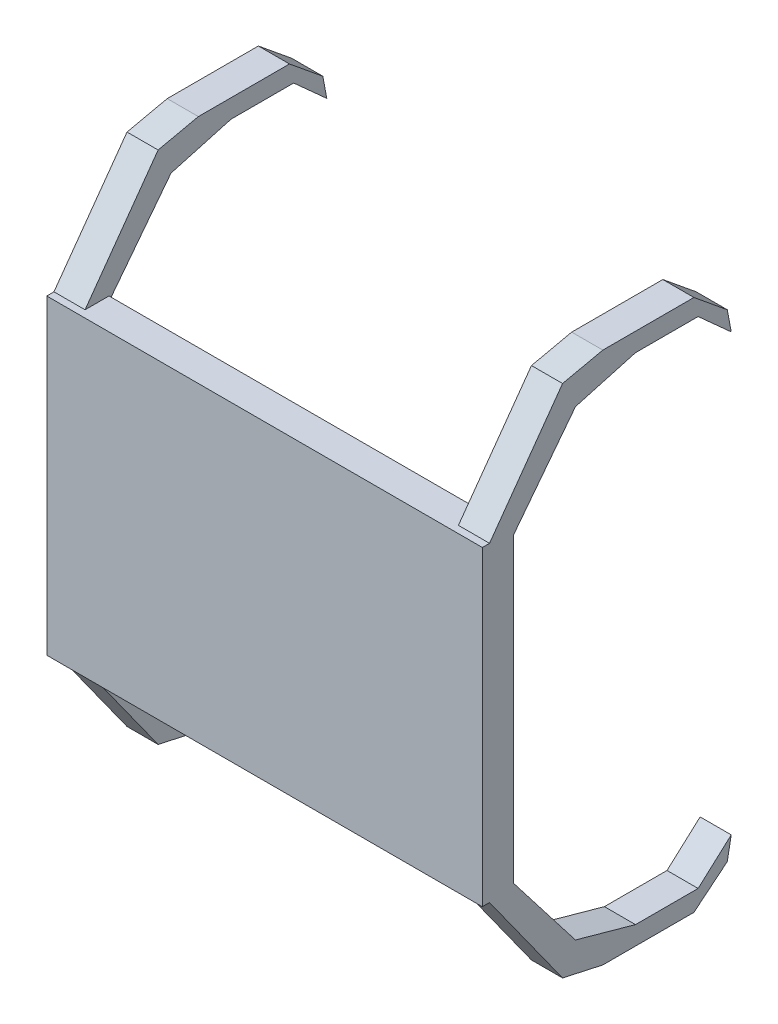
SolidWorks part; units mm, degrees
ref_plane "Front Plane" through (0, 0, 0) normal (0, 0, 1) x (1, 0, 0)
ref_plane "Top Plane" through (0, 0, 0) normal (0, 1, 0) x (1, 0, 0)
ref_plane "Right Plane" through (0, 0, 0) normal (1, 0, 0) x (0, 0, -1)
sketch "Sketch1" plane through (0, 0, 0) normal (0, 0, 1) x (1, 0, 0)
  line L0 (0, 0) -> (0, 23754.0671) construction
  line L1 (0, 0) -> (23754.0671, 0) construction
  line L2 (-35, 25) -> (35, 25)
  line L3 (35, 25) -> (35, -25)
  line L4 (-35, -25) -> (35, -25)
  line L5 (-35, 25) -> (-35, -25)
  point P9 (35, 0)
  point P11 (0, -25)
  point P12 (0, 25)
  dimension "D1" = 50
  dimension "D2" = 70
extrude "Boss-Extrude1" add sketch "Sketch1" along normal blind 5
sketch "Sketch2" plane through (-35, 0, 0) normal (-1, 0, 0) x (0, 0, 1)
  line L0 (0, 25) -> (0, -25) construction
  line L1 (0, 25) -> (0, 0)
  line L2 (0, 0) -> (-68.0514, 0) construction
  line L3 (3.8434, -25) -> (-7.8955, -41.3693)
  line L4 (-7.8955, -41.3693) -> (-14.3611, -42.7886)
  line L5 (-14.3611, -42.7886) -> (-29.0045, -42.7886)
  line L6 (-29.0045, -42.7886) -> (-34.3652, -38.4026)
  line L7 (-29.6771, -39.7964) -> (-35, -35)
  line L8 (-29.6771, -39.7964) -> (-19.6148, -39.7964)
  line L9 (-19.6148, -39.7964) -> (-9.9621, -37.1116)
  line L10 (-9.9621, -37.1116) -> (0, -24.2192)
  line L11 (-35, -35) -> (-34.3652, -38.4026)
  line L12 (0, -24.2192) -> (3.8434, -25)
  line L13 (5, -25) -> (0, -25) construction
  point P5 (-66.2985, -47.5562)
  point P14 (-66.2985, -41.2781)
  point P15 (-52.7536, -56.1207)
  point P16 (-64.705, -49.2685)
  point P17 (-18.8342, -46.0815)
  point P18 (-6.5413, -48.153)
  point P19 (-7.8756, -41.2781)
  point P20 (0, -25.525)
  point P21 (-25.1855, -45.444)
  point P22 (-13.7122, -39.0699)
  point P24 (-20.0863, -44.8066)
  point P25 (0, 0)
  point P26 (-32.9984, -46.251)
  point P27 (0, 0)
  point P28 (-35, -46.4333)
  point P29 (-29.1716, -48.9845)
  point P30 (-16.5065, -47.7089)
  point P31 (-35, -43.3353)
  point P32 (-31.0842, -47.8911)
  point P33 (-28.8982, -44.4287)
  point P34 (-16.0509, -45.9777)
  point P35 (-30.3561, -45.6132)
  point P36 (-34.3652, -42.3331)
  point P37 (-9.3994, -35)
  point P38 (0, 0)
  point P39 (-6.7571, -39.7818)
  point P40 (-35, -35)
  point P41 (0, 0)
  point P42 (0, -25.438)
  point P44 (3.8434, -25)
  point P47 (-9.9621, -37.1116)
  point P48 (0, -24.2192)
  dimension "D1" = 35
  dimension "D2" = 35
extrude "Boss-Extrude2" add sketch "Sketch2" against normal blind 5 contours L4 L5 L6 L11 L7 L8 L9 L10 L12 L3
mirror "Mirror1" about plane through (0, 0, 0) normal (0, 1, 0) of "Boss-Extrude2"
mirror "Mirror2" about plane through (0, 0, 0) normal (1, 0, 0) of "Mirror1", "Boss-Extrude2"
